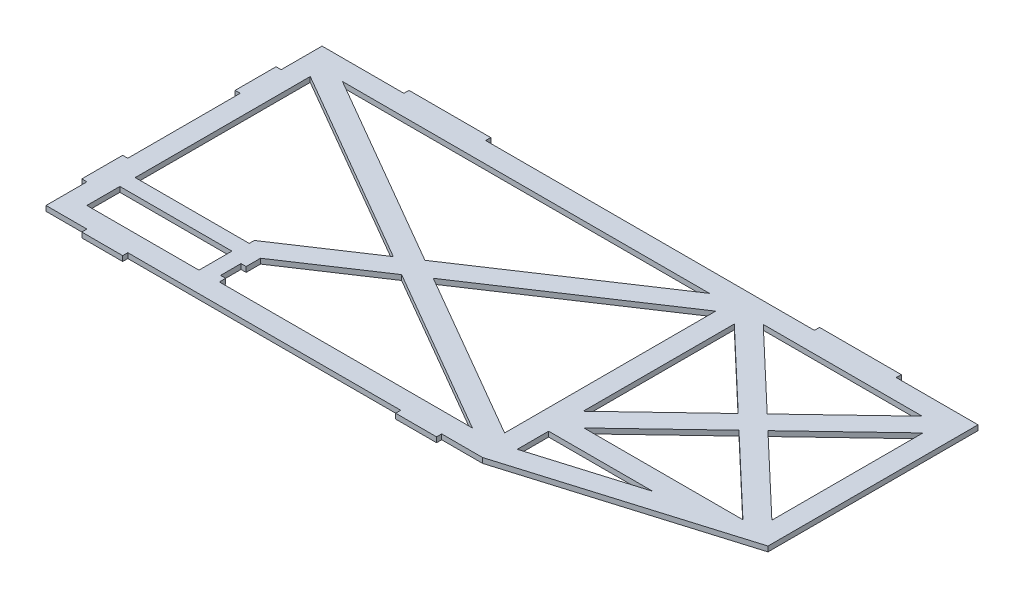
SolidWorks part; units mm, degrees
ref_plane "Front Plane" through (0, 0, 0) normal (0, 0, 1) x (1, 0, 0)
ref_plane "Top Plane" through (0, 0, 0) normal (0, 1, 0) x (1, 0, 0)
ref_plane "Right Plane" through (0, 0, 0) normal (1, 0, 0) x (0, 0, -1)
sketch "Sketch1" plane through (0, 0, 0) normal (0, 1, 0) x (1, 0, 0)
  line L0 (135.5725, -85.725) -> (271.8181, -44.704)
  line L1 (-135.5725, -85.725) -> (-110.1725, -85.725)
  line L2 (-135.5725, -85.725) -> (-135.5725, -60.325)
  line L3 (-135.5725, 85.725) -> (-84.7725, 85.725)
  line L4 (221.0181, 85.725) -> (271.8181, 85.725)
  line L5 (135.5725, 85.725) -> (170.2181, 85.725)
  line L6 (191.3026, 17.3355) -> (141.9225, -29.5938)
  line L7 (209.738, 17.3355) -> (259.1181, -29.5938)
  line L8 (271.8181, 85.725) -> (271.8181, -44.704)
  line L9 (141.9225, -51.054) -> (141.9225, -70.55)
  line L10 (-135.5725, -85.725) -> (-110.1725, -85.725)
  line L11 (-135.5725, -85.725) -> (-135.5725, -60.325)
  line L12 (-40.5765, -56.4388) -> (-40.5765, -47.4777)
  line L13 (-40.5765, -73.025) -> (-40.5765, -69.1388)
  line L14 (-110.2053, 73.025) -> (117.7523, 73.025)
  line L15 (-122.8725, 65.6863) -> (-122.8725, -43.0276)
  line L16 (-122.8725, -73.025) -> (-53.2765, -73.025)
  line L17 (129.2225, 65.3999) -> (129.2225, -65.6863)
  line L18 (151.1402, 73.025) -> (249.9004, 73.025)
  line L19 (141.9225, 64.2648) -> (141.9225, -29.5938)
  line L20 (151.1402, -38.354) -> (249.9004, -38.354)
  line L21 (259.1181, 64.2648) -> (259.1181, -29.5938)
  line L22 (141.9225, -70.55) -> (206.6758, -51.054)
  line L23 (206.6758, -51.054) -> (141.9225, -51.054)
  line L24 (-122.8725, 73.025) -> (129.2225, -73.025) construction
  line L25 (-122.8725, -73.025) -> (-53.2765, -73.025)
  line L26 (-122.8725, -73.025) -> (-122.8725, -52.5526)
  line L27 (-122.8725, -52.5526) -> (-53.2765, -52.5526)
  line L28 (-53.2765, -73.025) -> (-53.2765, -52.5526)
  line L29 (-40.5765, -39.8526) -> (129.2225, 73.025) construction
  line L30 (141.9225, 73.025) -> (259.1181, -38.354) construction
  line L31 (259.1181, 73.025) -> (141.9225, -38.354) construction
  line L32 (-122.8725, 65.6863) -> (-0.1976, -5.3848)
  line L33 (-110.2053, 73.025) -> (11.5998, 2.4578)
  line L34 (117.7523, 73.025) -> (11.5998, 2.4578)
  line L35 (129.2225, 65.3999) -> (23.8576, -4.6437)
  line L36 (151.1402, -38.354) -> (200.5203, 8.5753)
  line L37 (249.9004, 73.025) -> (200.5203, 26.0957)
  line L38 (141.9225, 64.2648) -> (191.3026, 17.3355)
  line L39 (151.1402, 73.025) -> (200.5203, 26.0957)
  line L40 (-135.5725, -85.725) -> (-135.5725, -88.9) construction
  line L41 (-135.5725, -88.9) -> (135.5725, -88.9) construction
  line L42 (135.5725, -88.9) -> (135.5725, -85.725) construction
  line L43 (-110.1725, -85.725) -> (-110.1725, -88.9)
  line L44 (-110.1725, -88.9) -> (-84.7725, -88.9)
  line L45 (-84.7725, -88.9) -> (-84.7725, -85.725)
  line L46 (84.7725, -85.725) -> (84.7725, -88.9)
  line L47 (84.7725, -88.9) -> (110.1725, -88.9)
  line L48 (110.1725, -88.9) -> (110.1725, -85.725)
  line L49 (-135.5725, 85.725) -> (-138.7475, 85.725) construction
  line L50 (-138.7475, 85.725) -> (-138.7475, -85.725) construction
  line L51 (-138.7475, -85.725) -> (-135.5725, -85.725) construction
  line L52 (-135.5725, -60.325) -> (-138.7475, -60.325)
  line L53 (-138.7475, -60.325) -> (-138.7475, -34.925)
  line L54 (-138.7475, -34.925) -> (-135.5725, -34.925)
  line L55 (-135.5725, 60.325) -> (-138.7475, 60.325)
  line L56 (-138.7475, 60.325) -> (-138.7475, 34.925)
  line L57 (-138.7475, 34.925) -> (-135.5725, 34.925)
  line L58 (-135.5725, 88.9) -> (271.8181, 88.9) construction
  line L59 (-84.7725, 85.725) -> (-84.7725, 88.9)
  line L60 (-84.7725, 88.9) -> (-33.9725, 88.9)
  line L61 (-33.9725, 88.9) -> (-33.9725, 85.725)
  line L62 (221.0181, 85.725) -> (221.0181, 88.9)
  line L63 (221.0181, 88.9) -> (170.2181, 88.9)
  line L64 (170.2181, 88.9) -> (170.2181, 85.725)
  line L65 (-43.7515, -39.8526) -> (-43.7515, -73.025) construction
  line L66 (-135.5725, -43.0276) -> (-40.5765, -43.0276) construction
  line L67 (-122.8725, -43.0276) -> (-52.0467, -43.0276)
  line L68 (-52.0467, -43.0276) -> (-52.0467, -39.8526)
  line L69 (-33.9725, 85.725) -> (135.5725, 85.725)
  line L70 (-40.5765, -56.4388) -> (-43.7515, -56.4388)
  line L71 (-43.7515, -56.4388) -> (-43.7515, -69.1388)
  line L72 (-43.7515, -69.1388) -> (-40.5765, -69.1388)
  line L73 (-135.5725, 60.325) -> (-135.5725, 85.725)
  line L74 (-122.8725, -52.5526) -> (-122.8725, -73.025)
  line L75 (-40.5765, -73.025) -> (116.5553, -73.025)
  line L76 (-135.5725, -34.925) -> (-135.5725, 34.925)
  line L77 (-84.7725, -85.725) -> (84.7725, -85.725)
  line L78 (200.5203, 8.5753) -> (249.9004, -38.354)
  line L79 (209.738, 17.3355) -> (259.1181, 64.2648)
  line L80 (110.1725, -85.725) -> (135.5725, -85.725)
  line L81 (12.0602, -12.4863) -> (116.5553, -73.025)
  line L82 (-0.1976, -5.3848) -> (-52.0467, -39.8526)
  line L83 (23.8576, -4.6437) -> (129.2225, -65.6863)
  line L84 (12.0602, -12.4863) -> (-40.5765, -47.4777)
  line L85 (-84.7725, -85.725) -> (-40.5765, -85.725)
  dimension "D1" = 407.3906
  dimension "D2" = 171.45
  dimension "D3" = 130.429
  dimension "D4" = 271.145
  dimension "D6" = 45.8724
  dimension "D7" = 12.7
  dimension "D8" = 12.7
  dimension "D9" = 12.7
  dimension "D11" = 12.7
  dimension "D12" = 12.7
  dimension "D16" = 12.7
  dimension "D18" = 12.7
  dimension "D19" = 6.35
  dimension "D20" = 6.35
  dimension "D21" = 6.35
  dimension "D22" = 6.35
  dimension "D23" = 6.35
  dimension "D24" = 6.35
  dimension "D25" = 6.35
  dimension "D26" = 6.35
  dimension "D27" = 3.175
  dimension "D28" = 25.4
  dimension "D29" = 25.4
  dimension "D30" = 25.4
  dimension "D32" = 3.175
  dimension "D33" = 25.4
  dimension "D34" = 25.4
  dimension "D35" = 25.4
  dimension "D36" = 25.4
  dimension "D37" = 3.175
  dimension "D38" = 50.8
  dimension "D39" = 50.8
  dimension "D40" = 50.8
  dimension "D41" = 50.8
  dimension "D42" = 3.175
  dimension "D44" = 12.7
  dimension "D45" = 16.5862
extrude "Boss-Extrude1" add sketch "Sketch1" along normal blind 3.175 contours L48 L80 L0 L8 L4 L62 L63 L64 L5 L69 L61 L60 L59 L3 L73 L55 L56 L57 L76 L54 L53 L52 L2 L1 L43 L44 L45 L77 L46 L47 L84 L81 L75 L13 L72 L71 L70 L12 L83 L35 L17 L7 L79 L21 L36 L78
